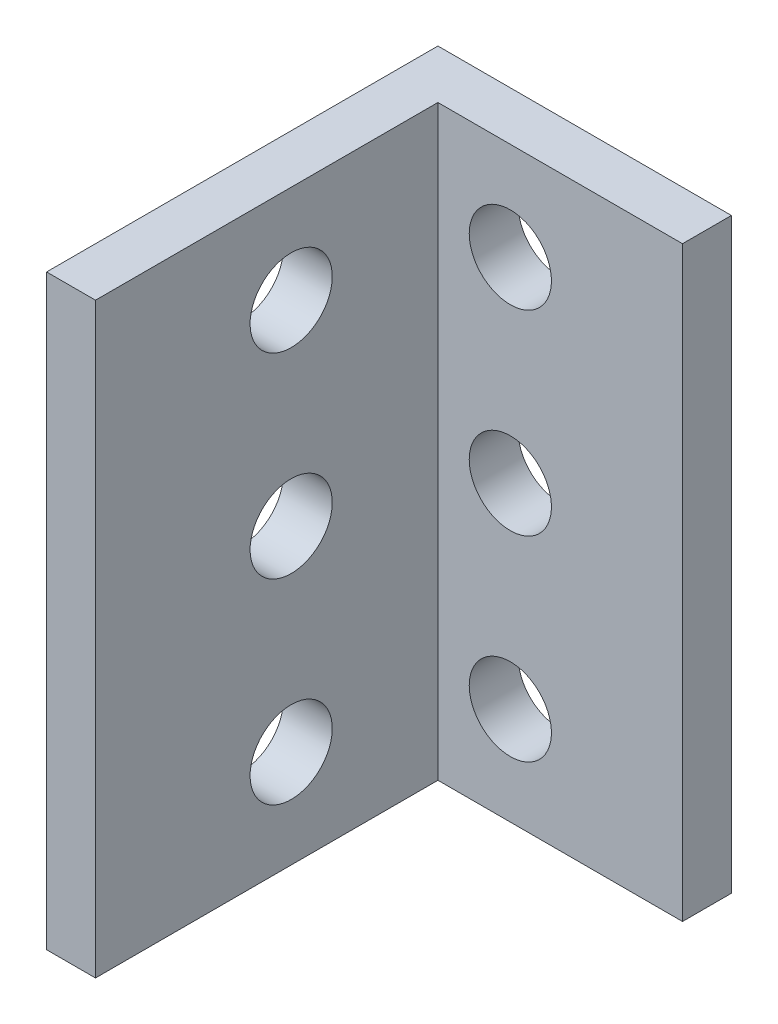
SolidWorks part; units mm, degrees
ref_plane "Front Plane" through (0, 0, 0) normal (0, 0, 1) x (1, 0, 0)
ref_plane "Top Plane" through (0, 0, 0) normal (0, 1, 0) x (1, 0, 0)
ref_plane "Right Plane" through (0, 0, 0) normal (1, 0, 0) x (0, 0, -1)
sketch "Sketch1" plane through (0, 0, 0) normal (0, 0, 1) x (1, 0, 0)
  line L0 (12.7, 19.05) -> (4.826, 19.05) construction
  line L1 (-6.35, 19.05) -> (12.7, 19.05)
  line L2 (-6.35, 19.05) -> (-6.35, -19.05)
  line L3 (-6.35, -19.05) -> (12.7, -19.05)
  line L4 (12.7, 19.05) -> (12.7, -19.05)
  line L7 (4.826, 19.05) -> (4.826, -19.05) construction
  line L8 (4.826, 0) -> (4.826, 12.7) construction
  line L9 (4.826, 0) -> (4.826, -12.7) construction
  line L10 (3.175, 19.05) -> (3.175, -19.05) construction
  line L11 (3.175, 19.05) -> (4.826, 19.05) construction
  circle A6 centre (1.524, -12.7) radius 2.667
  circle A7 centre (1.524, 0) radius 2.667
  circle A8 centre (1.524, 12.7) radius 2.667
  point P0 (0, 0)
  dimension "D3" = 12.7
  dimension "D5" = 12.7
  dimension "D4" = 7.874
  dimension "D1" = 38.1
  dimension "D2" = 19.05
extrude "Boss-Extrude1" add sketch "Sketch1" along normal blind 3.175
sketch "Sketch2" plane through (0, 0, 3.175) normal (0, 0, 1) x (1, 0, 0)
  line L0 (-6.35, -19.05) -> (12.7, -19.05) construction
  line L1 (-6.35, 19.05) -> (-3.175, 19.05)
  line L2 (-6.35, 19.05) -> (-6.35, -19.05)
  line L3 (-6.35, -19.05) -> (-3.175, -19.05)
  line L4 (-3.175, 19.05) -> (-3.175, -19.05)
  dimension "D1" = 3.175
extrude "Boss-Extrude2" add sketch "Sketch2" along normal blind 22.225
sketch "Sketch4" plane through (-3.175, 0, 0) normal (1, 0, 0) x (0, 0, -1)
  line L0 (0, 19.05) -> (-12.7, 19.05) construction
  line L1 (-25.4, 19.05) -> (-3.175, 19.05) construction
  line L2 (-12.7, 19.05) -> (-12.7, -19.05) construction
  line L3 (-25.4, -19.05) -> (-3.175, -19.05) construction
  line L4 (-12.7, 12.7) -> (-12.7, -12.7)
  circle A0 centre (-12.7, 0) radius 2.667
  circle A1 centre (-12.7, 12.7) radius 2.667
  circle A2 centre (-12.7, -12.7) radius 2.667
  point P13 (-12.7, 0)
  dimension "D2" = 5.334
  dimension "D4" = 5.334
  dimension "D5" = 5.334
  dimension "D1" = 12.7
  dimension "D3" = 25.4
extrude "Cut-Extrude1" cut sketch "Sketch4" against normal through all
